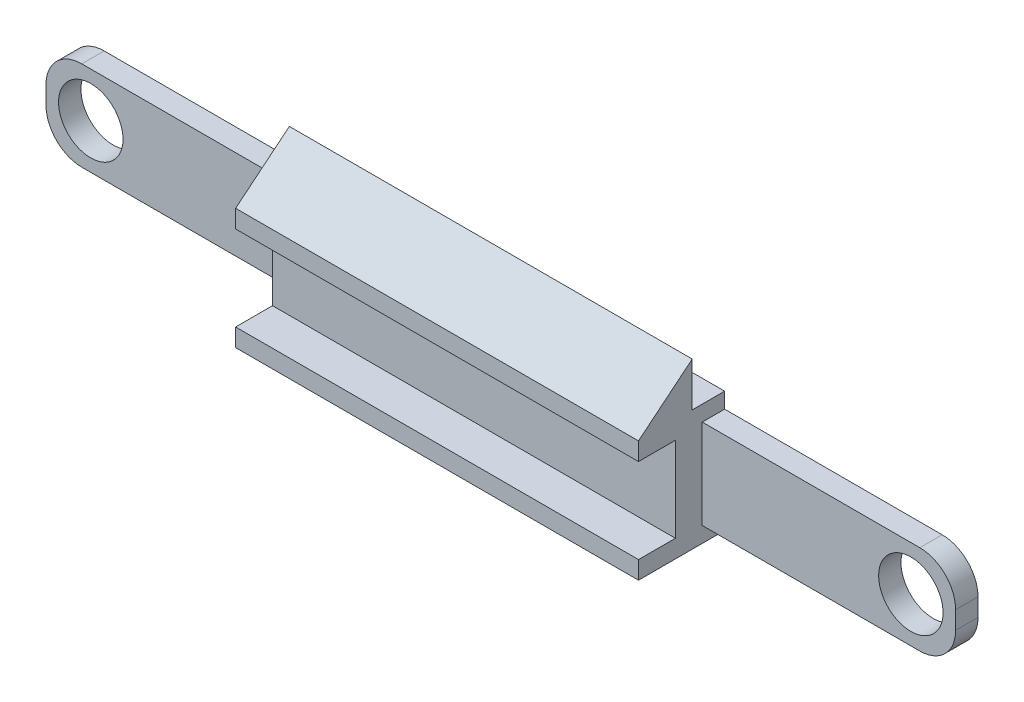
SolidWorks part; units mm, degrees
material "ABS PC"
ref_plane "Front Plane" through (0, 0, 0) normal (0, 0, 1) x (1, 0, 0)
ref_plane "Top Plane" through (0, 0, 0) normal (0, 1, 0) x (1, 0, 0)
ref_plane "Right Plane" through (0, 0, 0) normal (1, 0, 0) x (0, 0, -1)
sketch "Sketch1" plane through (0, 0, 0) normal (0, 0, 1) x (1, 0, 0)
  line L0 (0, 0) -> (0, 6.35) construction
  line L1 (59.436, -6.35) -> (-59.436, -6.35)
  line L2 (64.516, -1.27) -> (64.516, 1.27)
  line L3 (59.436, 6.35) -> (-59.436, 6.35)
  line L4 (-64.516, -1.27) -> (-64.516, 1.27)
  line L5 (64.516, -6.35) -> (-64.516, 6.35) construction
  line L6 (64.516, 6.35) -> (-64.516, -6.35) construction
  circle A0 centre (-58.166, 0) radius 4.572
  circle A1 centre (58.166, 0) radius 4.572
  arc A2 (59.436, -6.35) -> (64.516, -1.27) centre (59.436, -1.27) ccw
  arc A3 (64.516, 1.27) -> (59.436, 6.35) centre (59.436, 1.27) ccw
  arc A4 (-59.436, -6.35) -> (-64.516, -1.27) centre (-59.436, -1.27) cw
  arc A5 (-59.436, 6.35) -> (-64.516, 1.27) centre (-59.436, 1.27) ccw
  point P0 (0, 0)
  dimension "D1" = 6.35
  dimension "D2" = 9.144
  dimension "D3" = 58.166
  dimension "D5" = 5.08
  dimension "D4" = 6.35
extrude "Boss-Extrude1" add sketch "Sketch1" along normal blind 3.175
sketch "Sketch2" plane through (0, -6.35, 0) normal (0, -1, 0) x (1, 0, 0)
  line L0 (-59.436, 3.175) -> (59.436, 3.175) construction
  line L1 (-28.575, 3.175) -> (28.575, 3.175)
  line L2 (-28.575, 3.175) -> (-28.575, 0)
  line L3 (-28.575, 0) -> (28.575, 0)
  line L4 (28.575, 3.175) -> (28.575, 0)
  line L5 (-59.436, 0) -> (59.436, 0) construction
  point P8 (0, 0)
  dimension "D1" = 57.15
extrude "Boss-Extrude2" add sketch "Sketch2" along normal blind 2.2098
sketch "Sketch3" plane through (0, 0, 0) normal (1, 0, 0) x (0, 0, -1)
  line L0 (-3.175, -8.5598) -> (-12.2174, -8.5598)
  line L1 (-12.2174, -8.5598) -> (-12.2174, -6.0198)
  line L2 (-12.2174, -6.0198) -> (-6.985, -6.0198)
  line L3 (-6.985, -6.0198) -> (-6.985, 0.3302)
  line L4 (-6.985, 0.3302) -> (-3.175, 0.3302)
  line L5 (-3.175, 0.3302) -> (-3.175, -8.5598)
  dimension "D1" = 9.0424
  dimension "D2" = 8.89
  dimension "D3" = 3.81
  dimension "D4" = 2.54
extrude "Boss-Extrude3" add sketch "Sketch3" along normal mid plane 57.15
mirror "Mirror1" about plane through (0, 0, 0) normal (0, 1, 0) of "Boss-Extrude2", "Boss-Extrude3"
sketch "Sketch7" plane through (-28.575, 0, 0) normal (-1, 0, 0) x (0, 0, 1)
  line L0 (12.2174, 8.5598) -> (4.5974, 14.8082)
  line L1 (4.5974, 14.8082) -> (4.5974, 8.5598)
  line L2 (12.2174, 8.5598) -> (0, 8.5598) construction
  line L15 (12.2174, -6.0198) -> (6.985, -6.0198)
  line L16 (6.985, -6.0198) -> (6.985, 6.0198)
  line L17 (6.985, 6.0198) -> (12.2174, 6.0198)
  line L18 (12.2174, 6.0198) -> (12.2174, 8.5598)
  line L19 (12.2174, 8.5598) -> (0, 8.5598)
  line L20 (0, 8.5598) -> (0, 6.35)
  line L21 (0, 6.35) -> (3.175, 6.35)
  line L22 (3.175, 6.35) -> (3.175, -6.35)
  line L23 (3.175, -6.35) -> (0, -6.35)
  line L24 (0, -6.35) -> (0, -8.5598)
  line L25 (0, -8.5598) -> (12.2174, -8.5598)
  line L26 (12.2174, -8.5598) -> (12.2174, -6.0198)
  line L31 (12.2174, 8.5598) -> (4.5974, 8.5598)
  dimension "D1" = 7.62
  dimension "D2" = 6.2484
  dimension "D3" = 0
extrude "Boss-Extrude4" add sketch "Sketch7" against normal up to surface (57.15 mm away) up to face at (28.575, 0, 5.7658)
